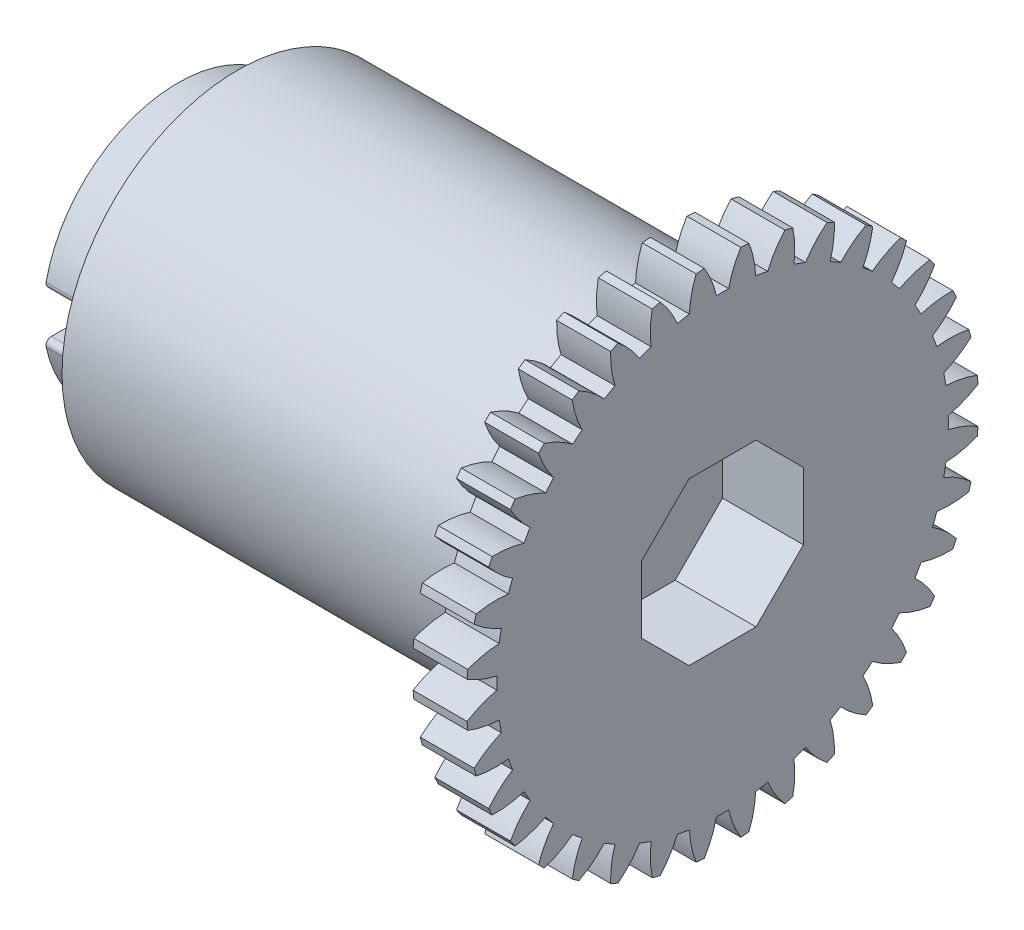
SolidWorks part; units mm, degrees
ref_plane "Alzado" through (0, 0, 0) normal (1, 0, 0) x (0, 1, 0)
ref_plane "Planta" through (0, 0, 0) normal (0, 0, 1) x (0, 1, 0)
ref_plane "Vista lateral" through (0, 0, 0) normal (0, 1, 0) x (-1, 0, 0)
sketch "Croquis1" plane through (0, 0, 0) normal (0, 0, 1) x (0, 1, 0)
  line L0 (0, 0) -> (0, 40.4) construction
  line L1 (0, 0) -> (19, 0)
  line L2 (19, 0) -> (19, 4)
  line L3 (19, 4) -> (13, 4)
  line L4 (13, 4) -> (13, 36)
  line L5 (13, 36) -> (10, 36)
  line L6 (10, 36) -> (10, 40.4)
  line L7 (10, 40.4) -> (0, 40.4)
  line L8 (0, 0) -> (0, 40.4)
  dimension "D1" = 40.4
  dimension "D2" = 38
  dimension "D3" = 4
  dimension "D4" = 26
  dimension "D5" = 32
  dimension "D6" = 20
revolve "Revolución1" add sketch "Croquis1" angle 360 about L0
sketch "Croquis2" plane through (0, 0, 0) normal (1, 0, 0) x (0, 1, 0)
  line L0 (0, 0) -> (0, 16.749) construction
  line L1 (0, 0) -> (1.656, 18.9277) construction
  line L2 (0, 0) -> (2.9084, 16.4945) construction
  arc A0 (1.3538, 18.9517) -> (0.4547, 16.7428) centre (7.4808, 15.1702) ccw
  arc A1 (0.4547, 16.7428) -> (-0.4547, 16.7428) centre (0, 0) ccw
  arc A2 (-0.4547, 16.7428) -> (-1.3538, 18.9517) centre (-7.4808, 15.1702) ccw
  arc A140 (4.6242, 18.4287) -> (3.3551, 16.4095) centre (10.0015, 13.6407) ccw
  arc A141 (3.3551, 16.4095) -> (2.4596, 16.5674) centre (0, 0) ccw
  arc A142 (2.4596, 16.5674) -> (1.9577, 18.8989) centre (-4.7329, 16.2388) ccw
  arc A145 (4.6242, 18.4287) -> (1.9577, 18.8989) centre (0, 0) ccw
  circle A146 centre (0, 0) radius 16.749 construction
  arc A147 (1.3538, 18.9517) -> (1.9577, 18.8989) centre (0, 0) ccw construction
  arc A148 (1.3538, 18.9517) -> (-1.3538, 18.9517) centre (0, 0) ccw
  circle M145 centre (0, 0) radius 19
  dimension "D2" = 33.498
  dimension "D3" = 19
  dimension "D4" = 7.2
  dimension "D1" = 5
  dimension "D5" = 2.7076
  dimension "D6" = 0.9093
extrude "Cortar-Extruir2" cut sketch "Croquis2" against normal blind 10 contours A2 A1 A0 M145
pattern_circular "MatrizC1" count 36 over 360 about axis through (0, 0, 0) along (1, 0, 0) of "Cortar-Extruir2"
sketch "Croquis3" plane through (0, 0, 0) normal (1, 0, 0) x (0, 1, 0)
  line L0 (0, 0) -> (13.975, 0) construction
  line L1 (2.4853, -6) -> (6, -2.4853)
  line L2 (6, -2.4853) -> (6, 2.4853)
  line L3 (6, 2.4853) -> (2.4853, 6)
  line L4 (2.4853, 6) -> (-2.4853, 6)
  line L5 (-2.4853, 6) -> (-6, 2.4853)
  line L6 (-6, 2.4853) -> (-6, -2.4853)
  line L7 (-6, -2.4853) -> (-2.4853, -6)
  line L8 (-2.4853, -6) -> (2.4853, -6)
  circle A0 centre (0, 0) radius 6 construction
  dimension "D1" = 12
extrude "Cortar-Extruir3" cut sketch "Croquis3" against normal blind 6
sketch "Croquis4" plane through (-40.4, 0, 0) normal (-1, 0, 0) x (0, -1, 0)
  line L0 (0, 0) -> (25.977, 0) construction
  line L1 (6, -2.4853) -> (6, 2.4853)
  line L2 (6, 2.4853) -> (2.4853, 6)
  line L3 (2.4853, 6) -> (-2.4853, 6)
  line L4 (-2.4853, 6) -> (-6, 2.4853)
  line L5 (-6, 2.4853) -> (-6, -2.4853)
  line L6 (-6, -2.4853) -> (-2.4853, -6)
  line L7 (-2.4853, -6) -> (2.4853, -6)
  line L8 (2.4853, -6) -> (6, -2.4853)
  circle A0 centre (0, 0) radius 6 construction
  dimension "D1" = 12
extrude "Cortar-Extruir4" cut sketch "Croquis4" against normal blind 6
sketch "Croquis5" plane through (-40.4, 0, 0) normal (-1, 0, 0) x (0, -1, 0)
  line L0 (0, 0) -> (0, 13) construction
  line L1 (-1.6, 7.6) -> (1.6, 7.6)
  line L2 (1.6, 7.6) -> (1.6, 9.8712)
  line L3 (2.4853, 6) -> (-2.4853, 6) construction
  line L4 (-1.6, 7.6) -> (-1.6, 9.8712)
  circle A0 centre (0, 0) radius 13 construction
  circle A1 centre (0, 0) radius 10 construction
  arc A2 (1.6, 9.8712) -> (-1.6, 9.8712) centre (0, 0) ccw
  point P14 (0, 7.6)
  dimension "D1" = 1.6
  dimension "D2" = 1.6
extrude "Cortar-Extruir5" cut sketch "Croquis5" against normal up to surface (4.4 mm away) up to face at (-36, 0, -10)
fillet "Redondeo1" radius 0.4 2 edges at (-38.2, 1.6, 9.8712) (-38.2, -1.6, 9.8712)
chamfer "Chaflán2" distance 0.4 angle 45 2 edges at (-38.2, -1.6, 7.6) (-38.2, 1.6, 7.6)
